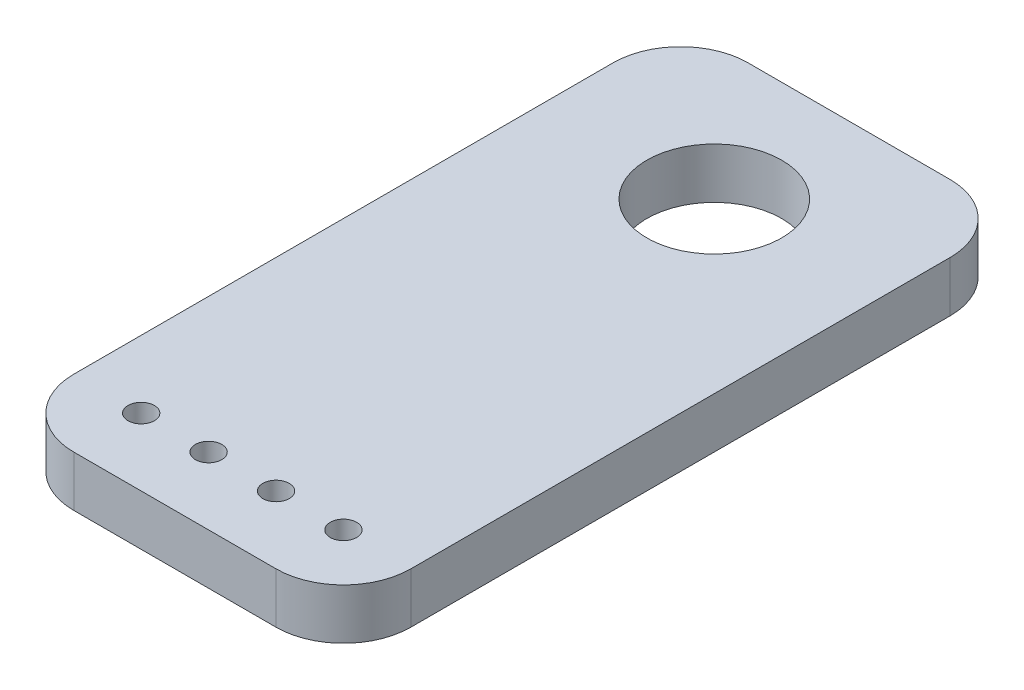
SolidWorks part; units mm, degrees
ref_plane "Front Plane" through (0, 0, 0) normal (0, 0, 1) x (1, 0, 0)
ref_plane "Top Plane" through (0, 0, 0) normal (0, 1, 0) x (1, 0, 0)
ref_plane "Right Plane" through (0, 0, 0) normal (1, 0, 0) x (0, 0, -1)
sketch "Sketch1" plane through (0, 0, 0) normal (0, 1, 0) x (1, 0, 0)
  line L0 (12.7, -114.3) -> (25.4, -114.3) construction
  line L1 (0, 0) -> (63.5, 0)
  line L2 (0, 0) -> (0, -127)
  line L3 (0, -127) -> (63.5, -127)
  line L4 (63.5, 0) -> (63.5, -127)
  circle A0 centre (31.75, -25.4) radius 12.7
  circle A1 centre (12.7, -114.3) radius 2.4892
  circle A2 centre (25.4, -114.3) radius 2.4892
  circle A3 centre (38.1, -114.3) radius 2.4892
  circle A4 centre (50.8, -114.3) radius 2.4892
  dimension "D3" = 25.4
  dimension "D4" = 25.4
  dimension "D5" = 31.75
  dimension "D6" = 4.9784
  dimension "D7" = 12.7
  dimension "D8" = 12.7
  dimension "D1" = 63.5
  dimension "D2" = 127
  dimension "D10" = 12.7
  dimension "D9" = 4
extrude "Boss-Extrude1" add sketch "Sketch1" along normal blind 9.525
fillet "Fillet1" radius 12.7 4 edges at (0, 4.7625, 127) (63.5, 4.7625, 127) (0, 4.7625, 0) (63.5, 4.7625, 0)
